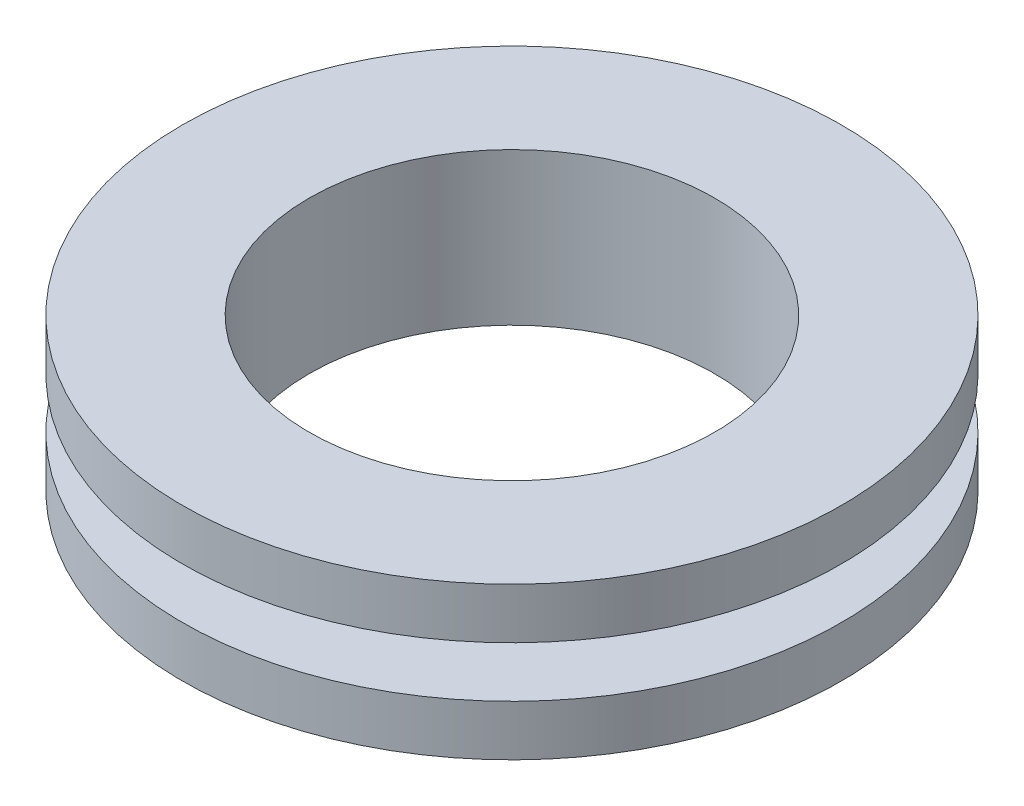
SolidWorks part; units mm, degrees
ref_plane "Plan de face" through (0, 0, 0) normal (0, 0, 1) x (1, 0, 0)
ref_plane "Plan de dessus" through (0, 0, 0) normal (0, 1, 0) x (1, 0, 0)
ref_plane "Plan de droite" through (0, 0, 0) normal (1, 0, 0) x (0, 0, -1)
sketch "Sketch1" plane through (0, 0, 0) normal (0, 0, 1) x (1, 0, 0)
  line L0 (0, 3.8002) -> (0, -3.8582) construction
  line L8 (5, 0.5) -> (5, -0.5)
  line L9 (5, -0.5) -> (6.5, -0.5)
  line L10 (6.5, -0.5) -> (6.5, -1.5)
  line L12 (5, 0.5) -> (6.5, 0.5)
  line L13 (6.5, 0.5) -> (6.5, 1.5)
  line L20 (6.5, 1.5) -> (4, 1.5)
  line L23 (4, 1.5) -> (4, -1.5)
  line L26 (4, -1.5) -> (6.5, -1.5)
  point P5 (5, 0)
  point P8 (0, 0)
  point P11 (0, 0)
  dimension "D3" = 1.5
  dimension "D5" = 4
  dimension "D1" = 5
  dimension "D2" = 1
  dimension "D7" = 3
revolve "Revolve1" add sketch "Sketch1" angle 360 about L0
